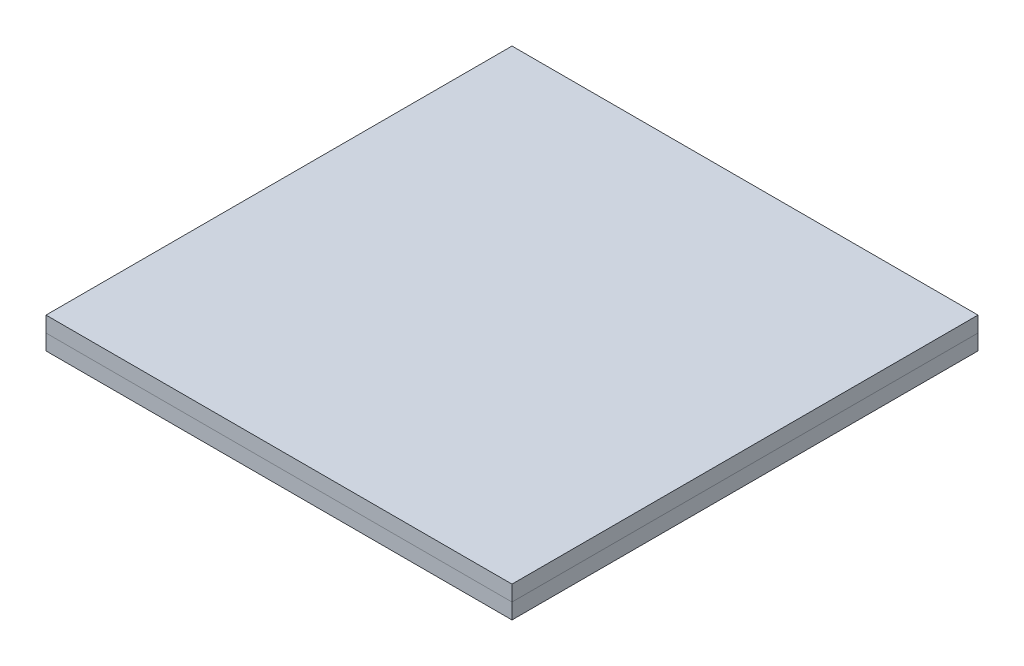
SolidWorks part; units mm, degrees
ref_plane "Front Plane" through (0, 0, 0) normal (0, 0, 1) x (1, 0, 0)
ref_plane "Top Plane" through (0, 0, 0) normal (0, 1, 0) x (1, 0, 0)
ref_plane "Right Plane" through (0, 0, 0) normal (1, 0, 0) x (0, 0, -1)
sketch "Sketch1" plane through (0, 0, 0) normal (0, 1, 0) x (1, 0, 0)
  line L1 (-19.05, -19.05) -> (19.05, -19.05)
  line L2 (-19.05, -19.05) -> (-19.05, 19.05)
  line L3 (-19.05, 19.05) -> (19.05, 19.05)
  line L4 (19.05, -19.05) -> (19.05, 19.05)
  line L5 (-19.05, -19.05) -> (19.05, 19.05) construction
  line L6 (-19.05, 19.05) -> (19.05, -19.05) construction
  point P0 (0, 0)
  dimension "D1" = 38.1
  dimension "D2" = 38.1
extrude "Boss-Extrude1" add sketch "Sketch1" along normal blind 2.54
ref_plane "Plane1" [suppressed] through (0, 1.27, 0) normal (0, -1, 0) x (-1, 0, 0)
split "Split1" trim tools "Plane1" bodies to split 101 resulting bodies 104 105
